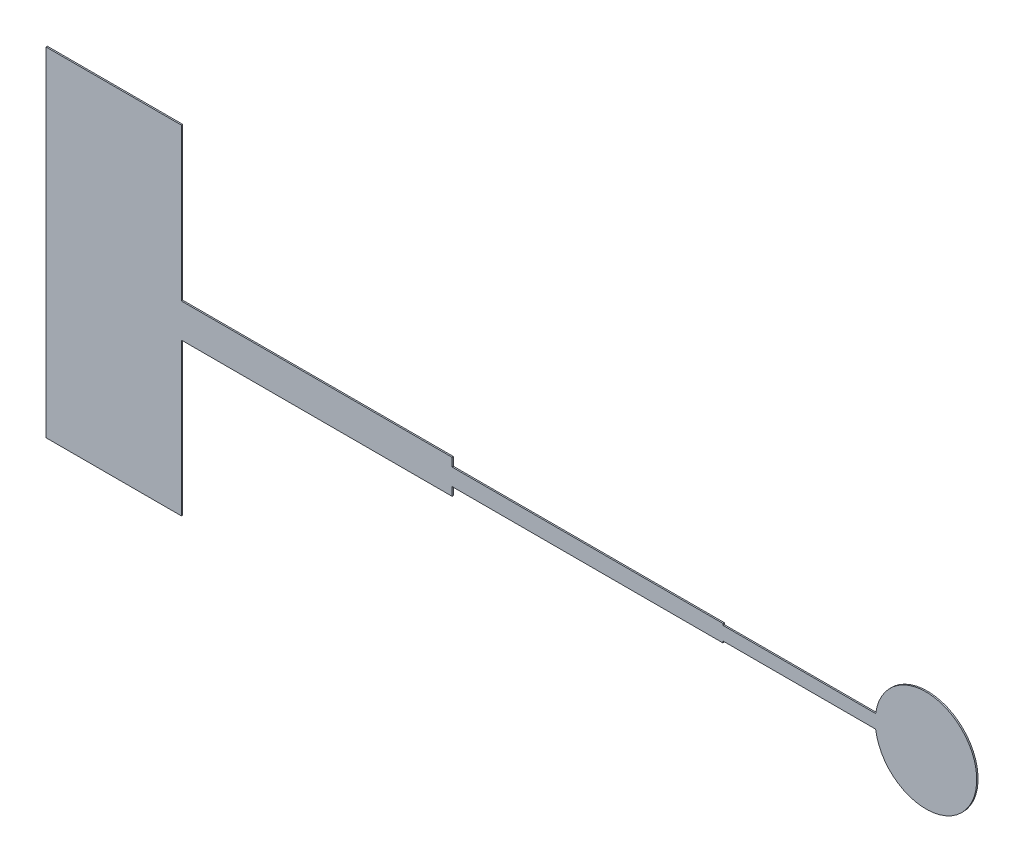
SolidWorks part; units mm, degrees
ref_plane "Front Plane" through (0, 0, 0) normal (0, 0, 1) x (1, 0, 0)
ref_plane "Top Plane" through (0, 0, 0) normal (0, 1, 0) x (1, 0, 0)
ref_plane "Right Plane" through (0, 0, 0) normal (1, 0, 0) x (0, 0, -1)
sketch "Sketch1" plane through (0, 0, 0) normal (0, 0, 1) x (1, 0, 0)
  line L0 (1000, 250) -> (5000, 250)
  line L1 (-1000, 2500) -> (1000, 2500)
  line L2 (-1000, 2500) -> (-1000, -2500)
  line L3 (-1000, -2500) -> (1000, -2500)
  line L4 (1000, 2500) -> (1000, 250)
  line L5 (-1000, 2500) -> (1000, -2500) construction
  line L6 (-1000, -2500) -> (1000, 2500) construction
  line L9 (1000, -250) -> (5000, -250)
  line L10 (5000, 250) -> (5000, 125)
  line L11 (-3000, 250) -> (5000, -250) construction
  line L12 (-3000, -250) -> (5000, 250) construction
  line L13 (5000, 125) -> (9000, 125)
  line L15 (5000, -125) -> (9000, -125)
  line L16 (9000, 125) -> (9000, 100)
  line L17 (1000, 125) -> (9000, -125) construction
  line L18 (1000, -125) -> (9000, 125) construction
  line L19 (9000, 100) -> (11256.6966, 100)
  line L21 (9000, -100) -> (11256.6966, -100)
  line L23 (6000, 100) -> (12000, -100) construction
  line L24 (6000, -100) -> (12000, 100) construction
  line L25 (1000, -250) -> (1000, -2500)
  line L26 (5000, -125) -> (5000, -250)
  line L27 (9000, -100) -> (9000, -125)
  arc A0 (11256.6966, -100) -> (11256.6966, 100) centre (12000, 0) ccw
  point P0 (0, 0)
  point P6 (1000, 0)
  point P11 (5000, 0)
  point P16 (9000, 0)
  dimension "D9" = 1500
  dimension "D1" = 2000
  dimension "D2" = 5000
  dimension "D3" = 500
  dimension "D4" = 4000
  dimension "D5" = 250
  dimension "D6" = 4000
  dimension "D7" = 200
extrude "Boss-Extrude1" add sketch "Sketch1" against normal blind 20
